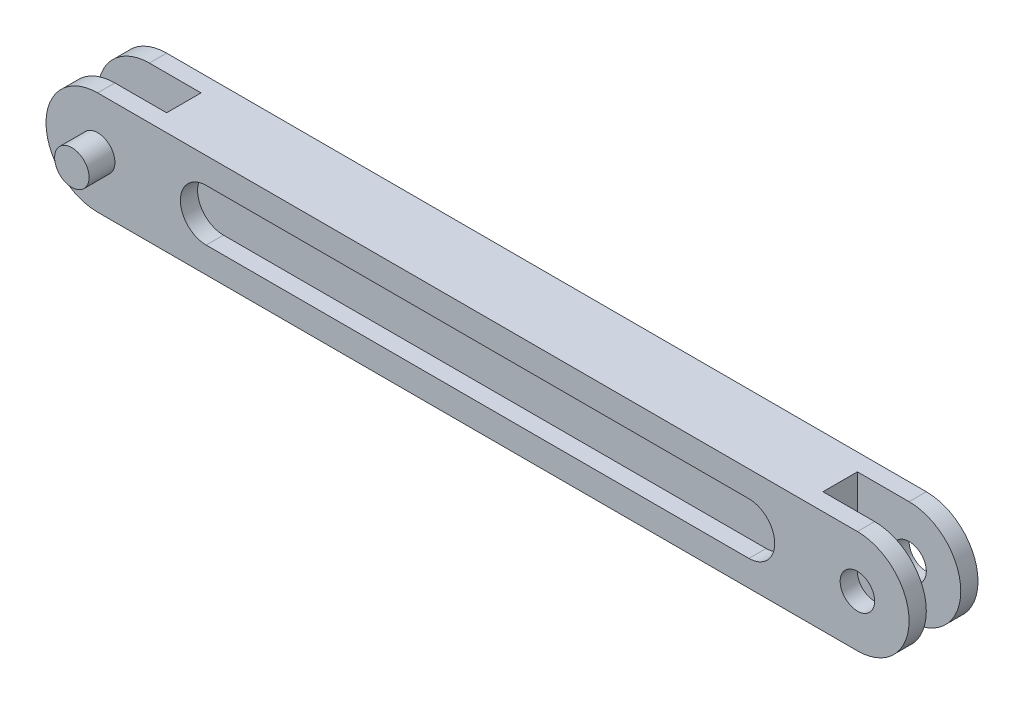
SolidWorks part; units mm, degrees
ref_plane "Front Plane" through (0, 0, 0) normal (0, 0, 1) x (1, 0, 0)
ref_plane "Top Plane" through (0, 0, 0) normal (0, 1, 0) x (1, 0, 0)
ref_plane "Right Plane" through (0, 0, 0) normal (1, 0, 0) x (0, 0, -1)
sketch "Sketch1" plane through (0, 0, 0) normal (0, 0, 1) x (1, 0, 0)
  line L0 (0, 0) -> (280, 0) construction
  line L1 (0, 19.05) -> (280, 19.05)
  line L2 (0, -19.05) -> (280, -19.05)
  arc A0 (0, 19.05) -> (0, -19.05) centre (0, 0) ccw
  arc A1 (280, -19.05) -> (280, 19.05) centre (280, 0) ccw
  circle A2 centre (0, 0) radius 6.35
  circle A3 centre (280, 0) radius 6.35
  point P3 (140, 0)
  dimension "D3" = 12.7
  dimension "D1" = 280
  dimension "D2" = 38.1
extrude "Boss-Extrude1" add sketch "Sketch1" along normal blind 25.4
sketch "Sketch2" plane through (0, 0, 25.4) normal (0, 0, 1) x (1, 0, 0)
  line L0 (40, 0) -> (240, 0) construction
  line L1 (40, 9.525) -> (240, 9.525)
  line L2 (40, -9.525) -> (240, -9.525)
  line L3 (0, 19.05) -> (280, 19.05)
  line L4 (0, 19.05) -> (280, 19.05) construction
  line L5 (280, -19.05) -> (0, -19.05)
  line L6 (280, -19.05) -> (0, -19.05) construction
  arc A0 (40, 9.525) -> (40, -9.525) centre (40, 0) ccw
  arc A1 (240, -9.525) -> (240, 9.525) centre (240, 0) ccw
  arc A2 (280, -19.05) -> (280, 19.05) centre (280, 0) ccw
  arc A3 (280, -19.05) -> (280, 19.05) centre (280, 0) ccw construction
  arc A4 (0, 19.05) -> (0, -19.05) centre (0, 0) ccw
  arc A5 (0, 19.05) -> (0, -19.05) centre (0, 0) ccw construction
  point P3 (140, 0)
  point P8 (140.8523, 0)
  point P15 (140, 19.05)
  dimension "D1" = 200
  dimension "D2" = 19.05
extrude "Cut-Extrude1" cut sketch "Sketch2" against normal blind 6.35
ref_plane "Plane1" through (0, 0, 12.7) normal (0, 0, 1) x (1, 0, 0)
mirror "Mirror1" about plane through (0, 0, 12.7) normal (0, 0, 1) of "Cut-Extrude1"
ref_plane "Plane2" through (-19.05, 0, 0) normal (-1, 0, 0) x (0, 0, 1)
sketch "Sketch3" plane through (-19.05, 0, 0) normal (-1, 0, 0) x (0, 0, 1)
  line L0 (0, -19.05) -> (0, 19.05)
  line L1 (0, -19.05) -> (0, 19.05) construction
  line L2 (0, 19.05) -> (25.4, 19.05)
  line L3 (0, 19.05) -> (25.4, 19.05) construction
  line L4 (25.4, 19.05) -> (25.4, -19.05)
  line L5 (25.4, 19.05) -> (25.4, -19.05) construction
  line L6 (25.4, -19.05) -> (0, -19.05)
  line L7 (25.4, -19.05) -> (0, -19.05) construction
  line L8 (6.35, -19.05) -> (6.35, 19.05)
  line L9 (6.35, -19.05) -> (19.05, -19.05)
  line L10 (6.35, 19.05) -> (19.05, 19.05)
  line L11 (19.05, -19.05) -> (19.05, 19.05)
  line L12 (6.35, -19.05) -> (19.05, 19.05) construction
  line L13 (6.35, 19.05) -> (19.05, -19.05) construction
  line L14 (12.7, 19.05) -> (12.7, -19.05) construction
  point P4 (12.7, 0)
  point P5 (12.7, 0)
  dimension "D1" = 12.7
extrude "Cut-Extrude2" cut sketch "Sketch3" against normal blind 38.1
ref_plane "Plane3" through (140, 0, 0) normal (-1, 0, 0) x (0, 0, 1)
mirror "Mirror2" about plane through (140, 0, 0) normal (-1, 0, 0) of "Cut-Extrude2"
sketch "Sketch5" plane through (0, 0, 25.4) normal (0, 0, 1) x (1, 0, 0)
  circle A0 centre (0, 0) radius 6.35
  point P6 (0, 0)
  dimension "D1" = 12.7
extrude "Boss-Extrude3" add sketch "Sketch5" along normal blind 9.525 and the other way blind 34.925
